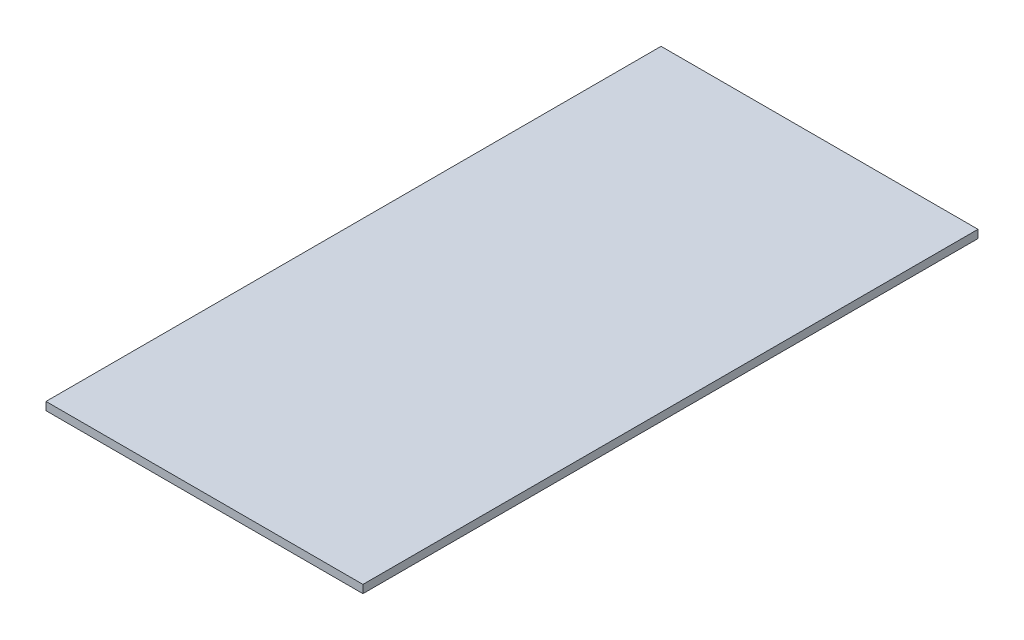
SolidWorks part; units mm, degrees
ref_plane "Front Plane" through (0, 0, 0) normal (0, 0, 1) x (1, 0, 0)
ref_plane "Top Plane" through (0, 0, 0) normal (0, 1, 0) x (1, 0, 0)
ref_plane "Right Plane" through (0, 0, 0) normal (1, 0, 0) x (0, 0, -1)
sketch "Sketch1" plane through (0, 0, 0) normal (0, 1, 0) x (1, 0, 0)
  line L1 (-59, -114.5) -> (59, -114.5)
  line L2 (-59, -114.5) -> (-59, 114.5)
  line L3 (-59, 114.5) -> (59, 114.5)
  line L4 (59, -114.5) -> (59, 114.5)
  line L5 (-59, -114.5) -> (59, 114.5) construction
  line L6 (-59, 114.5) -> (59, -114.5) construction
  point P0 (0, 0)
  dimension "D1" = 229
  dimension "D2" = 118
extrude "Boss-Extrude1" add sketch "Sketch1" along normal blind 3
